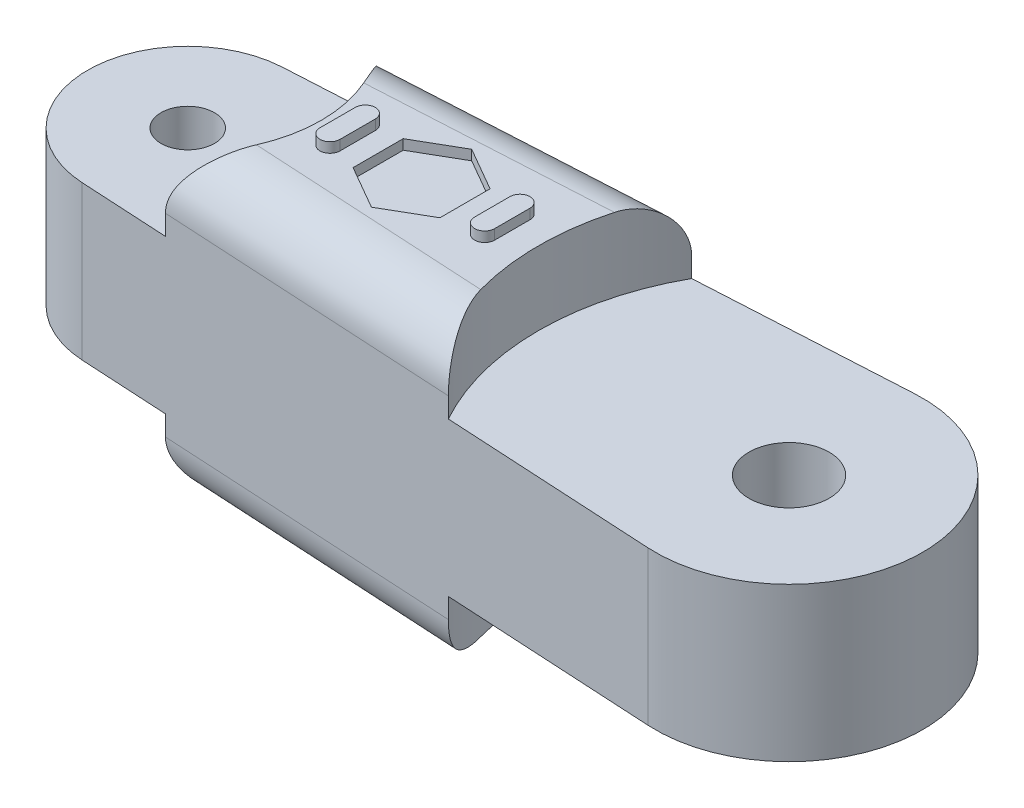
SolidWorks part; units mm, degrees
ref_plane "Ön Düzlem" through (0, 0, 0) normal (0, 0, 1) x (1, 0, 0)
ref_plane "Üst Düzlem" through (0, 0, 0) normal (0, 1, 0) x (1, 0, 0)
ref_plane "Sağ Düzlem" through (0, 0, 0) normal (1, 0, 0) x (0, 0, -1)
sketch "Sketch1" plane through (0, 0, 0) normal (0, 1, 0) x (1, 0, 0)
  line L0 (-90.8333, 14.9768) -> (-1.1111, 19.9691)
  line L1 (-90.8333, -14.9768) -> (-1.1111, -19.9691)
  arc A0 (-1.1111, -19.9691) -> (-1.1111, 19.9691) centre (0, 0) ccw
  arc A1 (-90.8333, 14.9768) -> (-90.8333, -14.9768) centre (-90, 0) ccw
  dimension "D1" = 30
  dimension "D2" = 40
  dimension "D3" = 90
extrude "Boss-Extrude1" add sketch "Sketch1" along normal mid plane 45
sketch "Sketch2" plane through (0, 22.5, 0) normal (0, 1, 0) x (1, 0, 0)
  circle A0 centre (-90, 0) radius 20
  circle A1 centre (0, 0) radius 37.5
  dimension "D1" = 40
  dimension "D2" = 75
extrude "Cut-Extrude2" cut sketch "Sketch2" against normal blind 11
ref_plane "Plane1" through (0, 0, 0) normal (0, 1, 0) x (1, 0, 0)
mirror "Mirror1" about plane through (0, 0, 0) normal (0, 1, 0) of "Cut-Extrude2"
fillet "Fillet1" radius 8 4 edges at (-55.2043, 22.5, 16.9593) (-55.2043, 22.5, -16.9593) (-55.2043, -22.5, -16.9593) (-55.2043, -22.5, 16.9593)
sketch "Sketch3" plane through (0, 11.5, 0) normal (0, 1, 0) x (1, 0, 0)
  circle A0 centre (0, 0) radius 6
  circle A1 centre (-90, 0) radius 4
  dimension "D1" = 12
  dimension "D2" = 8
extrude "Cut-Extrude3" cut sketch "Sketch3" against normal blind 44.5
sketch "Sketch5" plane through (0, 22.5, 0) normal (0, 1, 0) x (1, 0, 0)
  line L0 (-90, 0) -> (0, 0) construction
  line L2 (-55, -7.5056) -> (-48.5, -3.7528)
  line L3 (-48.5, -3.7528) -> (-48.5, 3.7528)
  line L4 (-48.5, 3.7528) -> (-55, 7.5056)
  line L5 (-55, 7.5056) -> (-61.5, 3.7528)
  line L6 (-61.5, 3.7528) -> (-61.5, -3.7528)
  line L7 (-61.5, -3.7528) -> (-55, -7.5056)
  circle A0 centre (-55, 0) radius 6.5 construction
  point P0 (-90, 0)
  point P1 (0, 0)
  dimension "D1" = 13
  dimension "D2" = 35
extrude "Cut-Extrude6" cut sketch "Sketch5" against normal blind 1.5
sketch "Sketch6" plane through (0, 22.5, 0) normal (0, 1, 0) x (1, 0, 0)
  line L0 (-61.5, 0) -> (-70, 0) construction
  line L1 (-61.5, 3.7528) -> (-61.5, -3.7528) construction
  line L2 (-48.5, 0) -> (-37.5, 0) construction
  line L3 (-48.5, -3.7528) -> (-48.5, 3.7528) construction
  line L4 (-66.1407, 2.7169) -> (-66.1407, -2.5674) construction
  line L5 (-64.6407, 2.7169) -> (-64.6407, -2.5674)
  line L6 (-67.6407, 2.7169) -> (-67.6407, -2.5674)
  line L7 (-43, 2.7268) -> (-43, -2.5574) construction
  line L8 (-41.5, 2.7268) -> (-41.5, -2.5574)
  line L9 (-44.5, 2.7268) -> (-44.5, -2.5574)
  arc A0 (-77.625, -15.7118) -> (-77.625, 15.7118) centre (-90, 0) ccw construction
  arc A1 (-32.7836, 18.2068) -> (-32.7836, -18.2068) centre (0, 0) ccw construction
  arc A2 (-64.6407, 2.7169) -> (-67.6407, 2.7169) centre (-66.1407, 2.7169) ccw
  arc A3 (-67.6407, -2.5674) -> (-64.6407, -2.5674) centre (-66.1407, -2.5674) ccw
  arc A4 (-41.5, 2.7268) -> (-44.5, 2.7268) centre (-43, 2.7268) ccw
  arc A5 (-44.5, -2.5574) -> (-41.5, -2.5574) centre (-43, -2.5574) ccw
  point P16 (-66.1407, 0.0747)
  point P23 (-43, 0.0847)
  dimension "D1" = 3
  dimension "D2" = 3
  dimension "D3" = 3.86
  dimension "D4" = 5.5
extrude "Boss-Extrude2" add sketch "Sketch6" along normal blind 1.5
mirror "Mirror2" about plane through (0, 0, 0) normal (0, 1, 0) of "Boss-Extrude2", "Cut-Extrude6"
sketch "Sketch8" plane through (0, -11.5, 0) normal (0, -1, 0) x (1, 0, 0)
  point P0 (-90, 0)
  point P1 (-60.9341, -22.0894)
